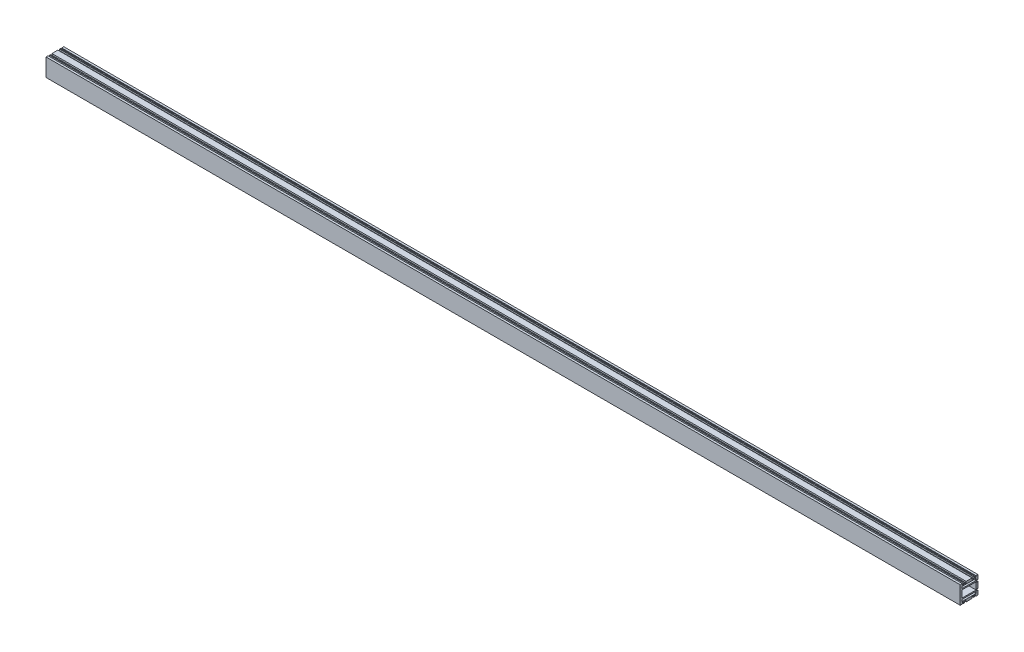
SolidWorks part; units mm, degrees
ref_plane "前视基准面" through (0, 0, 0) normal (0, 0, 1) x (1, 0, 0)
ref_plane "上视基准面" through (0, 0, 0) normal (0, 1, 0) x (1, 0, 0)
ref_plane "右视基准面" through (0, 0, 0) normal (1, 0, 0) x (0, 0, -1)
sketch "草图1" plane through (0, 0, 0) normal (1, 0, 0) x (0, 0, -1)
  line L0 (-15, 15) -> (15, -15) construction
  line L1 (-15, 15) -> (-11.5, 15)
  line L2 (-15, 15) -> (-15, -15)
  line L3 (-15, -15) -> (-11.5, -15)
  line L4 (15, 15) -> (15, 8)
  line L5 (15, 15) -> (-15, -15) construction
  line L6 (-11.5, 15) -> (-11.5, 13.5)
  line L7 (-11.5, 13.5) -> (-11, 13.5)
  line L8 (-11, 13.5) -> (-11, 12)
  line L9 (-11, 12) -> (-9.5, 12)
  line L10 (-9.5, 12) -> (-9.5, 15)
  line L11 (-9.5, 15) -> (-8, 15)
  line L12 (-8, 15) -> (-8, 12.5)
  line L13 (-8, 12.5) -> (-5, 12.5)
  line L14 (-5, 12.5) -> (-5, 15)
  line L15 (-5, 15) -> (5, 15)
  line L16 (0, 21.5201) -> (0, -18.309) construction
  line L17 (0, 55) -> (0, -55) construction
  line L18 (5, 12.5) -> (5, 15)
  line L19 (8, 12.5) -> (5, 12.5)
  line L20 (8, 15) -> (8, 12.5)
  line L21 (9.5, 15) -> (8, 15)
  line L22 (9.5, 12) -> (9.5, 15)
  line L23 (11, 12) -> (9.5, 12)
  line L24 (11, 13.5) -> (11, 12)
  line L25 (11.5, 13.5) -> (11, 13.5)
  line L26 (11.5, 15) -> (11.5, 13.5)
  line L27 (8, 15) -> (9.5, 15)
  line L28 (11.5, 15) -> (15, 15)
  line L29 (-19.8303, 0) -> (22.13, 0) construction
  line L30 (55, 0) -> (-55, 0) construction
  line L31 (8, -15) -> (9.5, -15)
  line L32 (11.5, -15) -> (11.5, -13.5)
  line L33 (11.5, -13.5) -> (11, -13.5)
  line L34 (11, -13.5) -> (11, -12)
  line L35 (11, -12) -> (9.5, -12)
  line L36 (9.5, -12) -> (9.5, -15)
  line L37 (9.5, -15) -> (8, -15)
  line L38 (8, -15) -> (8, -12.5)
  line L39 (8, -12.5) -> (5, -12.5)
  line L40 (5, -12.5) -> (5, -15)
  line L41 (-5, -15) -> (5, -15)
  line L42 (-5, -12.5) -> (-5, -15)
  line L43 (-8, -12.5) -> (-5, -12.5)
  line L44 (-8, -15) -> (-8, -12.5)
  line L45 (-9.5, -15) -> (-8, -15)
  line L46 (-9.5, -12) -> (-9.5, -15)
  line L47 (-11, -12) -> (-9.5, -12)
  line L48 (-11, -13.5) -> (-11, -12)
  line L49 (-11.5, -13.5) -> (-11, -13.5)
  line L50 (-11.5, -15) -> (-11.5, -13.5)
  line L51 (-9.5, -15) -> (-8, -15)
  line L52 (-5, -15) -> (5, -15)
  line L53 (8, -15) -> (9.5, -15)
  line L54 (11.5, -15) -> (15, -15)
  line L55 (15, 8) -> (12.5, 8)
  line L56 (12.5, 8) -> (12.5, 5)
  line L57 (12.5, 5) -> (15, 5)
  line L58 (12.5, -5) -> (15, -5)
  line L59 (12.5, -8) -> (12.5, -5)
  line L60 (15, -8) -> (12.5, -8)
  line L61 (15, 5) -> (15, -5)
  line L62 (15, -8) -> (15, -15)
  line L63 (12, -10.5) -> (12, -8.5)
  line L64 (-11.5, 11) -> (11.5, 11)
  line L65 (-12, 10.5) -> (-12, 8.5)
  line L66 (-11.5, 8) -> (11.5, 8)
  line L67 (12, 10.5) -> (12, 8.5)
  line L68 (-11.5, -8) -> (11.5, -8)
  line L69 (-12, -10.5) -> (-12, -8.5)
  line L70 (-11.5, -11) -> (11.5, -11)
  line L72 (-11.75, 6) -> (11.75, 6)
  line L73 (-11.75, 6) -> (-11.75, -6)
  line L74 (-11.75, -6) -> (11.75, -6)
  line L75 (11.75, 6) -> (11.75, -6)
  arc A0 (12, 8.5) -> (11.5, 8) centre (11.5, 8.5) cw
  arc A1 (11.5, 11) -> (12, 10.5) centre (11.5, 10.5) cw
  arc A2 (-11.5, 11) -> (-12, 10.5) centre (-11.5, 10.5) ccw
  arc A3 (-11.5, 8) -> (-12, 8.5) centre (-11.5, 8.5) cw
  arc A8 (-11.5, -8) -> (-12, -8.5) centre (-11.5, -8.5) ccw
  arc A9 (-11.5, -11) -> (-12, -10.5) centre (-11.5, -10.5) cw
  arc A10 (11.5, -11) -> (12, -10.5) centre (11.5, -10.5) ccw
  arc A11 (12, -8.5) -> (11.5, -8) centre (11.5, -8.5) ccw
  point P69 (12, 11)
  point P72 (-12, 11)
  point P77 (-11, -13.5)
  point P80 (11, -13.5)
  point P83 (11, 13.5)
  point P86 (-11, 13.5)
  point P99 (-12, -11)
  point P100 (12, -11)
  dimension "D17" = 0.5
  dimension "D1" = 3.5
  dimension "D2" = 1.5
  dimension "D3" = 0.5
  dimension "D4" = 1.5
  dimension "D5" = 3
  dimension "D6" = 30
  dimension "D7" = 30
  dimension "D8" = 1.5
  dimension "D9" = 2.5
  dimension "D10" = 3
  dimension "D11" = 2.5
  dimension "D12" = 7
  dimension "D13" = 3
  dimension "D14" = 4
  dimension "D15" = 3
  dimension "D16" = 24
  dimension "D19" = 23.5
  dimension "D20" = 12
extrude "凸台-拉伸1" add sketch "草图1" along normal mid plane 1542
